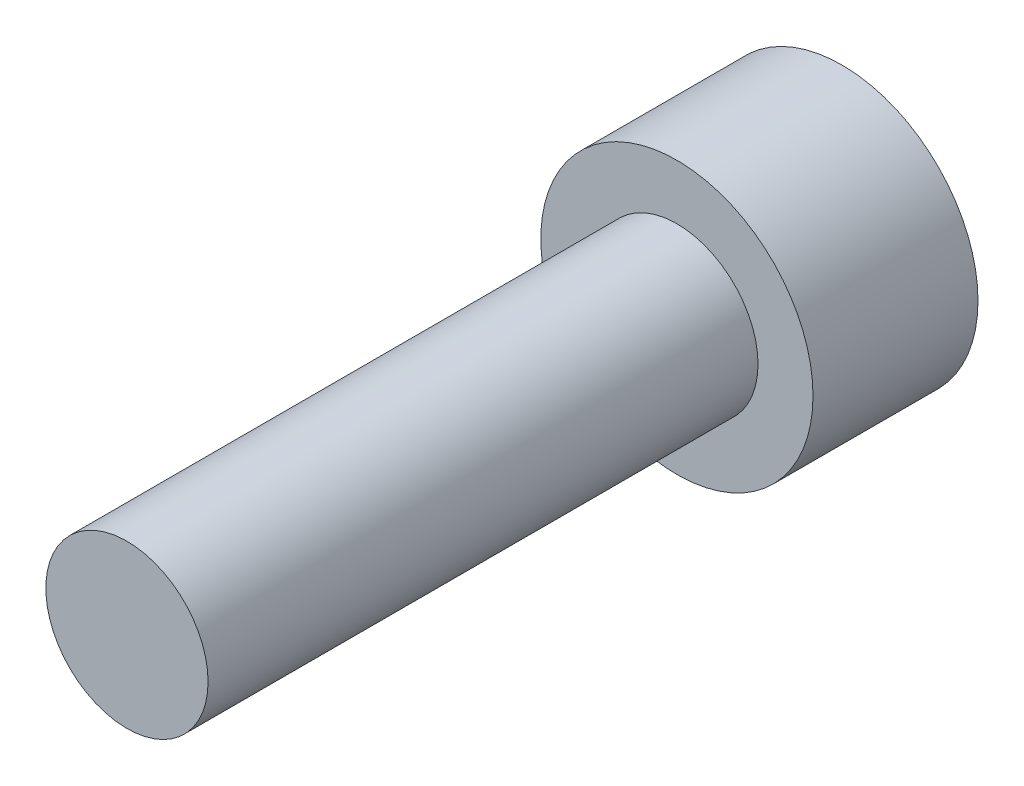
SolidWorks part; units mm, degrees
ref_plane "Front" through (0, 0, 0) normal (0, 0, 1) x (1, 0, 0)
ref_plane "Top" through (0, 0, 0) normal (0, 1, 0) x (1, 0, 0)
ref_plane "Right" through (0, 0, 0) normal (1, 0, 0) x (0, 0, -1)
sketch "Skizze1" plane through (0, 0, 0) normal (0, 0, 1) x (1, 0, 0)
  circle A0 centre (0, 0) radius 4.95
  dimension "D1" = 9.9
extrude "Aufsatz-Linear austragen1" add sketch "Skizze1" along normal blind 6
sketch "Skizze2" plane through (0, 0, 6) normal (0, 0, 1) x (1, 0, 0)
  circle A0 centre (0, 0) radius 2.95
  dimension "D1" = 5.9
extrude "Aufsatz-Linear austragen2" add sketch "Skizze2" along normal blind 20
